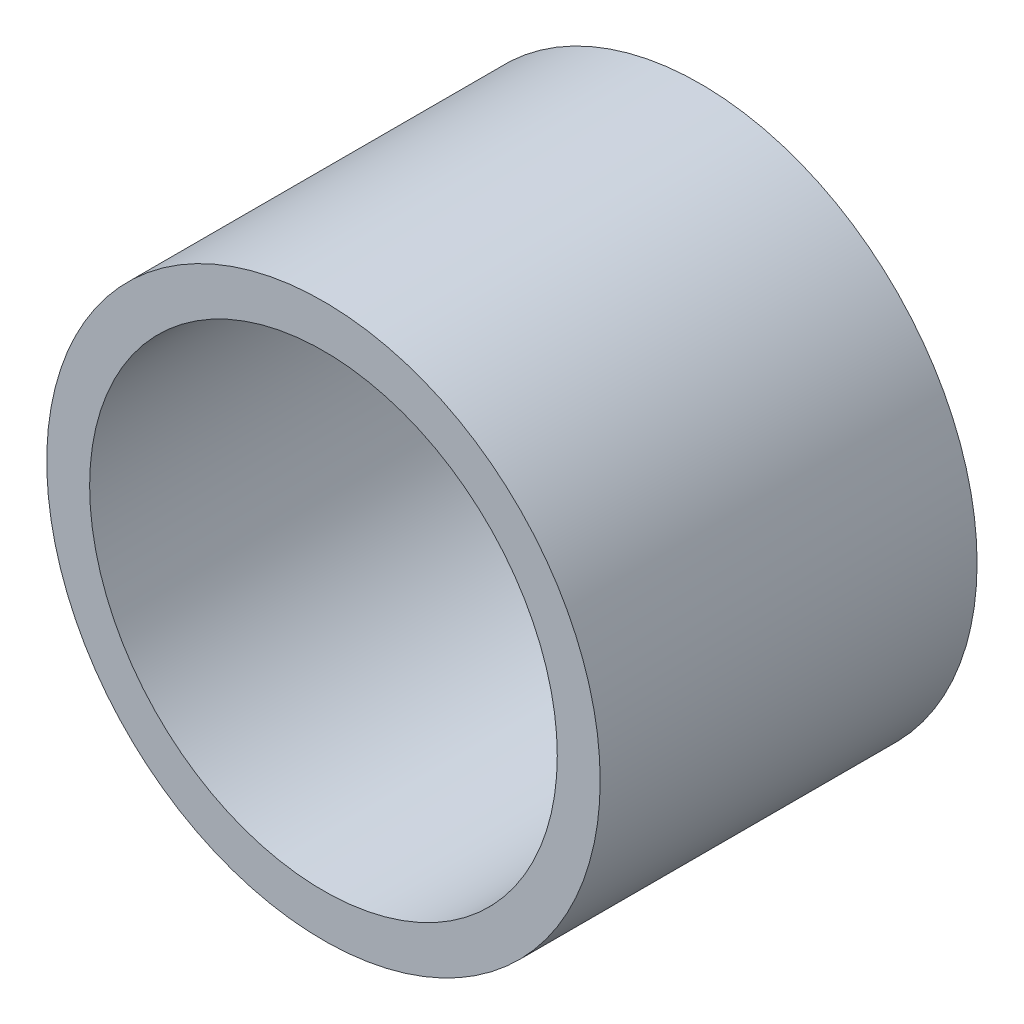
SolidWorks part; units mm, degrees
ref_plane "Front Plane" through (0, 0, 0) normal (0, 0, 1) x (1, 0, 0)
ref_plane "Top Plane" through (0, 0, 0) normal (0, 1, 0) x (1, 0, 0)
ref_plane "Right Plane" through (0, 0, 0) normal (1, 0, 0) x (0, 0, -1)
sketch "Sketch1" plane through (0, 0, 0) normal (0, 0, 1) x (1, 0, 0)
  circle A0 centre (0, 0) radius 50
  circle A1 centre (0, 0) radius 42.25
  dimension "D1" = 100
  dimension "D2" = 84.5
extrude "Boss-Extrude1" add sketch "Sketch1" along normal blind 68.1
